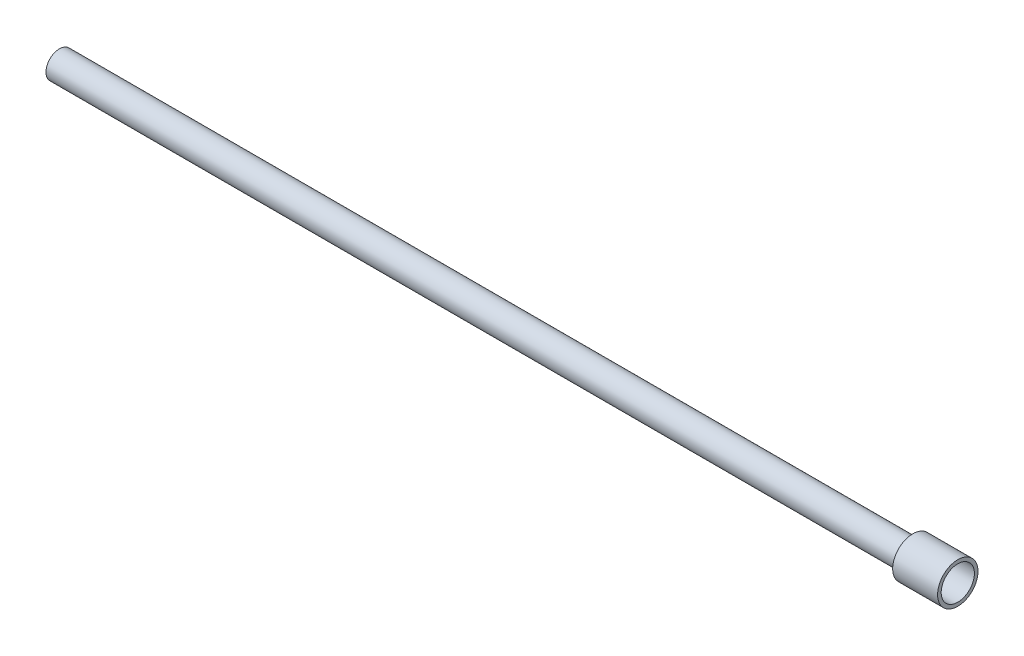
SolidWorks part; units mm, degrees
ref_plane "Front Plane" through (0, 0, 0) normal (0, 0, 1) x (1, 0, 0)
ref_plane "Top Plane" through (0, 0, 0) normal (0, 1, 0) x (1, 0, 0)
ref_plane "Right Plane" through (0, 0, 0) normal (1, 0, 0) x (0, 0, -1)
sketch "Sketch1" plane through (0, 0, 0) normal (1, 0, 0) x (0, 0, -1)
  circle A0 centre (0, 0) radius 75
  circle A1 centre (0, 0) radius 37.5
  dimension "D1" = 150
  dimension "D2" = 75
extrude "Boss-Extrude1" add sketch "Sketch1" along normal blind 4750
sketch "Sketch2" plane through (4750, 0, 0) normal (1, 0, 0) x (0, 0, -1)
  circle A0 centre (0, 0) radius 112.5
  circle A1 centre (0, 0) radius 92.5
  dimension "D1" = 225
  dimension "D2" = 185
extrude "Boss-Extrude2" add sketch "Sketch2" along normal blind 250 separate body
